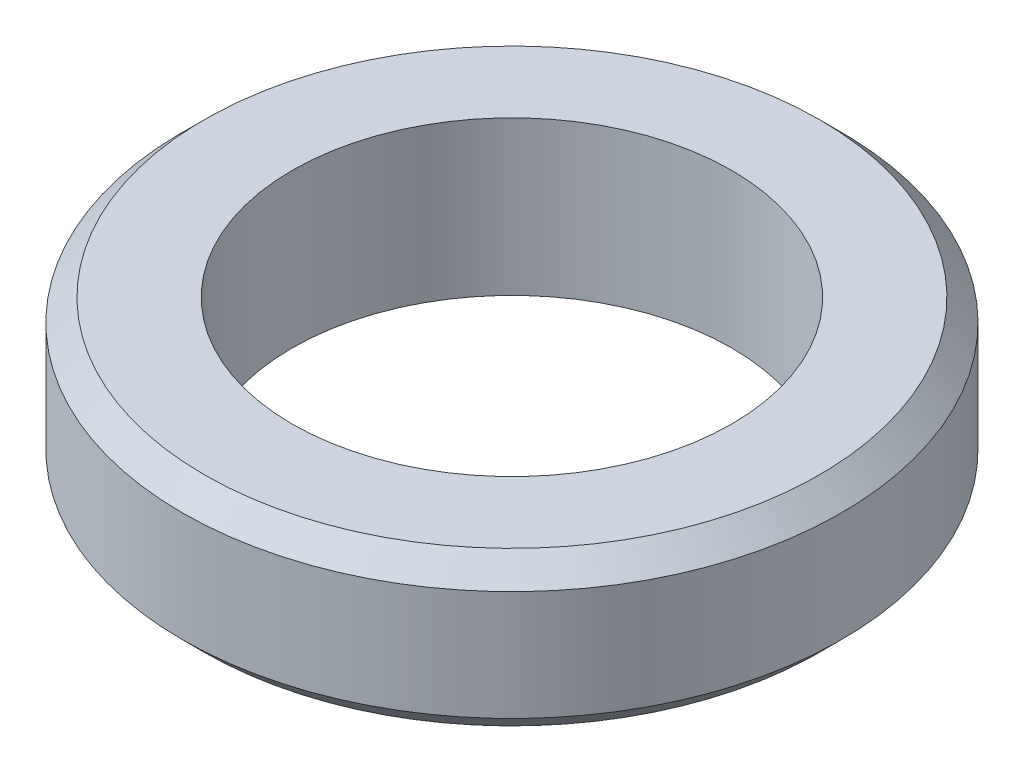
SolidWorks part; units mm, degrees
ref_plane "Front Plane" through (0, 0, 0) normal (0, 0, 1) x (1, 0, 0)
ref_plane "Top Plane" through (0, 0, 0) normal (0, 1, 0) x (1, 0, 0)
ref_plane "Right Plane" through (0, 0, 0) normal (1, 0, 0) x (0, 0, -1)
sketch "Sketch1" plane through (0, 0, 0) normal (0, 1, 0) x (1, 0, 0)
  circle A0 centre (0, 0) radius 5
  circle A1 centre (0, 0) radius 7.5
  dimension "D1" = 10
  dimension "D2" = 15
extrude "Corpo Ø15×3.5" add sketch "Sketch1" along normal blind 3.5
chamfer "Chanfros 0.5×45°" distance 0.5 angle 45 2 edges at (0, 0, 7.5) (0, 3.5, 7.5)
